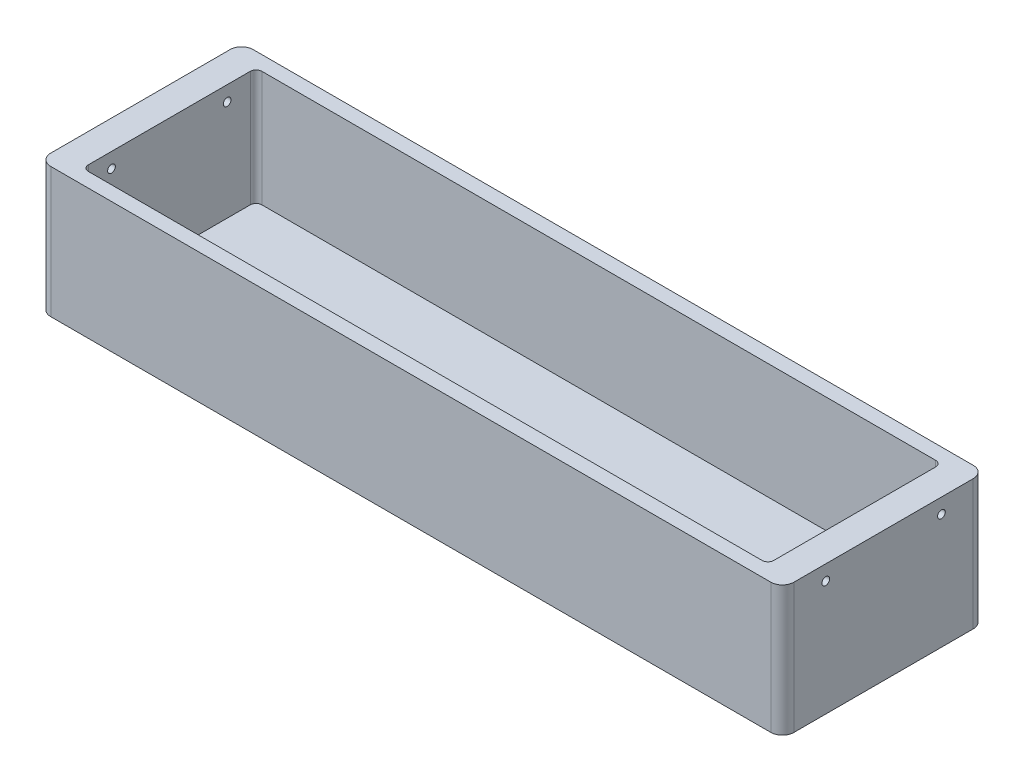
SolidWorks part; units mm, degrees
ref_plane "Front Plane" through (0, 0, 0) normal (0, 0, 1) x (1, 0, 0)
ref_plane "Top Plane" through (0, 0, 0) normal (0, 1, 0) x (1, 0, 0)
ref_plane "Right Plane" through (0, 0, 0) normal (1, 0, 0) x (0, 0, -1)
sketch "Sketch1" plane through (0, 0, 0) normal (0, 1, 0) x (1, 0, 0)
  line L1 (-131.445, -31.75) -> (131.445, -31.75) construction
  line L2 (-131.445, -31.75) -> (-131.445, 31.75) construction
  line L3 (-131.445, 31.75) -> (131.445, 31.75) construction
  line L4 (131.445, -31.75) -> (131.445, 31.75) construction
  line L5 (0, 31.75) -> (0, -31.75) construction
  line L6 (-131.445, 0) -> (131.445, 0) construction
  line L11 (-163.195, -44.45) -> (163.195, -44.45)
  line L12 (-163.195, -44.45) -> (-163.195, 44.45)
  line L13 (-163.195, 44.45) -> (163.195, 44.45)
  line L14 (163.195, -44.45) -> (163.195, 44.45)
  line L15 (0, 44.45) -> (0, -44.45) construction
  line L16 (-163.195, 0) -> (163.195, 0) construction
  line L17 (-150.495, -38.1) -> (150.495, -38.1)
  line L18 (-150.495, -38.1) -> (-150.495, 38.1)
  line L23 (0, 38.1) -> (0, -38.1) construction
  line L24 (-150.495, 0) -> (150.495, 0) construction
  line L25 (-150.495, 38.1) -> (150.495, 38.1)
  line L26 (150.495, -38.1) -> (150.495, 38.1)
  line L27 (0, 38.1) -> (0, -38.1) construction
  line L28 (-150.495, 0) -> (150.495, 0) construction
  point P0 (0, 0)
  point P4 (0, 0)
  point P8 (0, 0)
  point P13 (0, 0)
  dimension "D1" = 131.445
  dimension "D2" = 63.5
  dimension "D4" = 6.35
  dimension "D5" = 12.7
  dimension "D3" = 19.05
  dimension "D6" = 6.35
extrude "Boss-Extrude1" add sketch "Sketch1" along normal blind 50.8
sketch "Sketch2" plane through (0, 0, 0) normal (0, -1, 0) x (1, 0, 0)
  line L4 (163.195, -44.45) -> (163.195, 44.45)
  line L5 (163.195, 44.45) -> (-163.195, 44.45)
  line L6 (-163.195, 44.45) -> (-163.195, -44.45)
  line L7 (-163.195, -44.45) -> (163.195, -44.45)
  line L8 (163.195, -44.45) -> (163.195, 44.45)
  line L9 (163.195, 44.45) -> (-163.195, 44.45)
  line L10 (-163.195, 44.45) -> (-163.195, -44.45)
  line L11 (-163.195, -44.45) -> (163.195, -44.45)
  dimension "D1" = 0
extrude "Boss-Extrude2" add sketch "Sketch2" along normal blind 6.35
sketch "Sketch3" plane through (0, -6.35, 0) normal (0, -1, 0) x (1, 0, 0)
  line L0 (55, 0) -> (-55, 0) construction
  circle A0 centre (-106, 7.5) radius 3.1
  circle A1 centre (-106, -7.5) radius 3.1
  dimension "D2" = 6.2
  dimension "D1" = 106
  dimension "D3" = 7.5
extrude "Cut-Extrude1" cut sketch "Sketch3" against normal through all
sketch "Sketch4" plane through (163.195, 0, 0) normal (1, 0, 0) x (0, 0, -1)
  line L0 (44.45, -6.35) -> (-44.45, -6.35) construction
  line L1 (0, 55) -> (0, -55) construction
  circle A0 centre (25.4, 44.2239) radius 1.6875
  circle A1 centre (-25.4, 44.2239) radius 1.6875
  dimension "D2" = 3.375
  dimension "D1" = 50.5739
  dimension "D3" = 25.4
extrude "Cut-Extrude3" cut sketch "Sketch4" against normal up to surface (313.69 mm away)
mirror "Mirror2" about plane through (0, 0, 0) normal (1, 0, 0) of "Cut-Extrude3"
fillet "Fillet1" radius 5.08 4 edges at (163.195, 22.225, -44.45) (163.195, 22.225, 44.45) (-163.195, 22.225, -44.45) (-163.195, 22.225, 44.45)
fillet "Fillet2" radius 2.54 4 edges at (150.495, 25.4, 38.1) (150.495, 25.4, -38.1) (-150.495, 25.4, 38.1) (-150.495, 25.4, -38.1)
